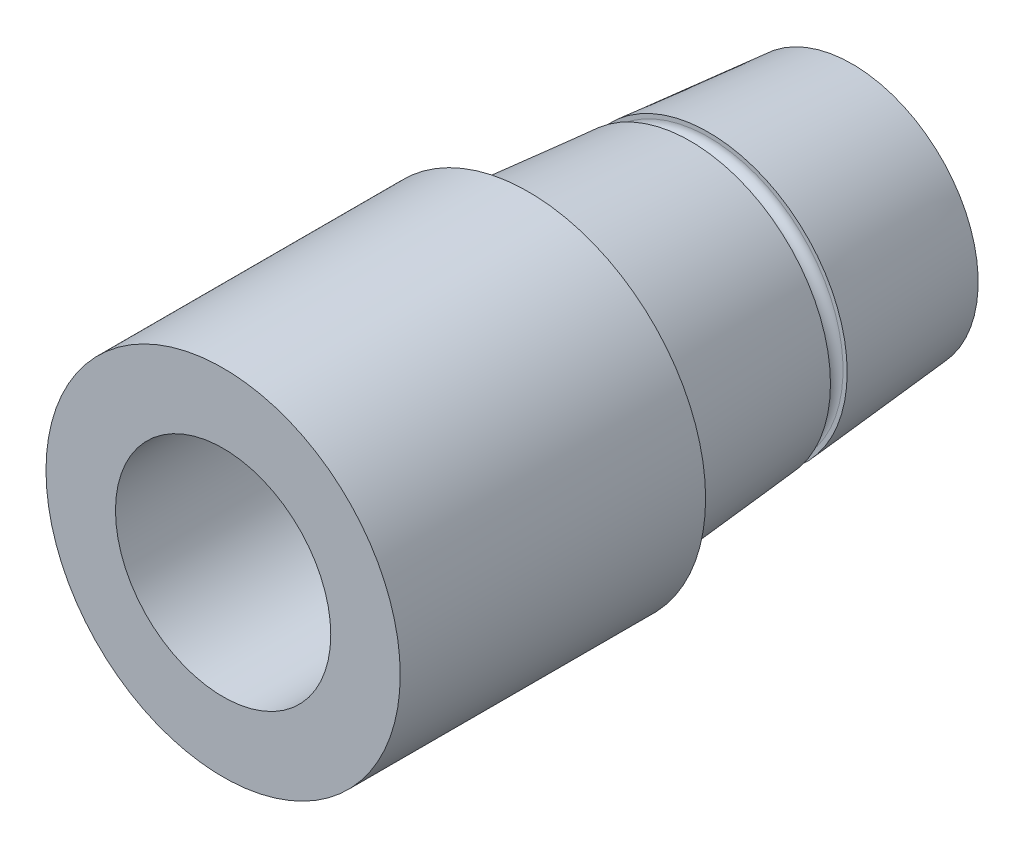
SolidWorks part; units mm, degrees
ref_plane "Front Plane" through (0, 0, 0) normal (0, 0, 1) x (1, 0, 0)
ref_plane "Top Plane" through (0, 0, 0) normal (0, 1, 0) x (1, 0, 0)
ref_plane "Right Plane" through (0, 0, 0) normal (1, 0, 0) x (0, 0, -1)
sketch "Sketch1" plane through (0, 0, -50) normal (0, 0, -1) x (-1, 0, 0)
  circle A0 centre (0, 0) radius 20.6256
  circle A4 centre (0, 0) radius 20.6256
extrude "Boss-Extrude1" add sketch "Sketch1" against normal blind 53 draft 5 draft outward yes
sketch "Sketch2" plane through (0, 0, -50) normal (0, 0, -1) x (-1, 0, 0)
  circle A3 centre (0, 0) radius 17.6256
  circle A4 centre (0, 0) radius 17.6256
  dimension "D1" = 3
extrude "Cut-Extrude1" cut sketch "Sketch2" against normal through all
sketch "Эскиз1" plane through (0, 0, 0) normal (1, 0, 0) x (0, 0, -1)
  line L3 (8.9876, 0) -> (-20.241, 0) construction
  line L4 (26.5, 22) -> (26.5, 23.5)
  line L5 (26.5, 23.5) -> (23.5, 23.5)
  line L6 (23.5, 23.5) -> (23.5, 22)
  line L7 (26.5, 20.5) -> (23.5, 20.5) construction
  arc A0 (23.5, 22) -> (26.5, 22) centre (25, 22) ccw
  point P6 (25, 20.5)
  dimension "D1" = 3
  dimension "D2" = 20.5
  dimension "D3" = 25
revolve "Вырез-Повернуть1" cut sketch "Эскиз1" angle 360 about L3
sketch "Эскиз4" plane through (0, 0, 3) normal (0, 0, 1) x (1, 0, 0)
  circle A0 centre (0, 0) radius 29 construction
  circle A1 centre (0, 0) radius 29
  circle A2 centre (0, 0) radius 17.6256 construction
  circle A3 centre (0, 0) radius 17.6256
extrude "Бобышка-Вытянуть1" add sketch "Эскиз4" along normal blind 50
